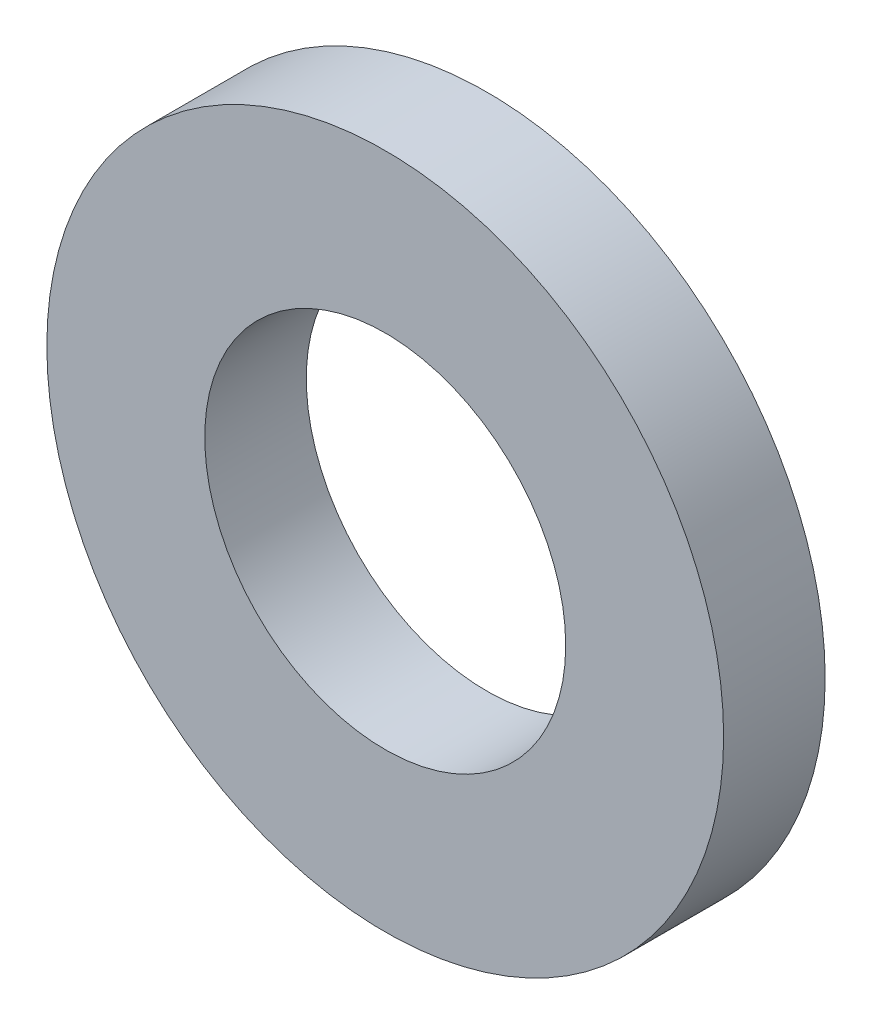
SolidWorks part; units mm, degrees
material "Stainless Steel (ferritic)"
ref_plane "Front Plane" through (0, 0, 0) normal (0, 0, 1) x (1, 0, 0)
ref_plane "Top Plane" through (0, 0, 0) normal (0, 1, 0) x (1, 0, 0)
ref_plane "Right Plane" through (0, 0, 0) normal (1, 0, 0) x (0, 0, -1)
sketch "Sketch1" plane through (0, 0, 0) normal (0, 0, 1) x (1, 0, 0)
  circle A0 centre (0, 0) radius 6
  circle A1 centre (0, 0) radius 3.2
  dimension "OD" = 12
  dimension "ID1" = 6.4
extrude "Boss-Extrude1" add sketch "Sketch1" along normal blind 1.8
